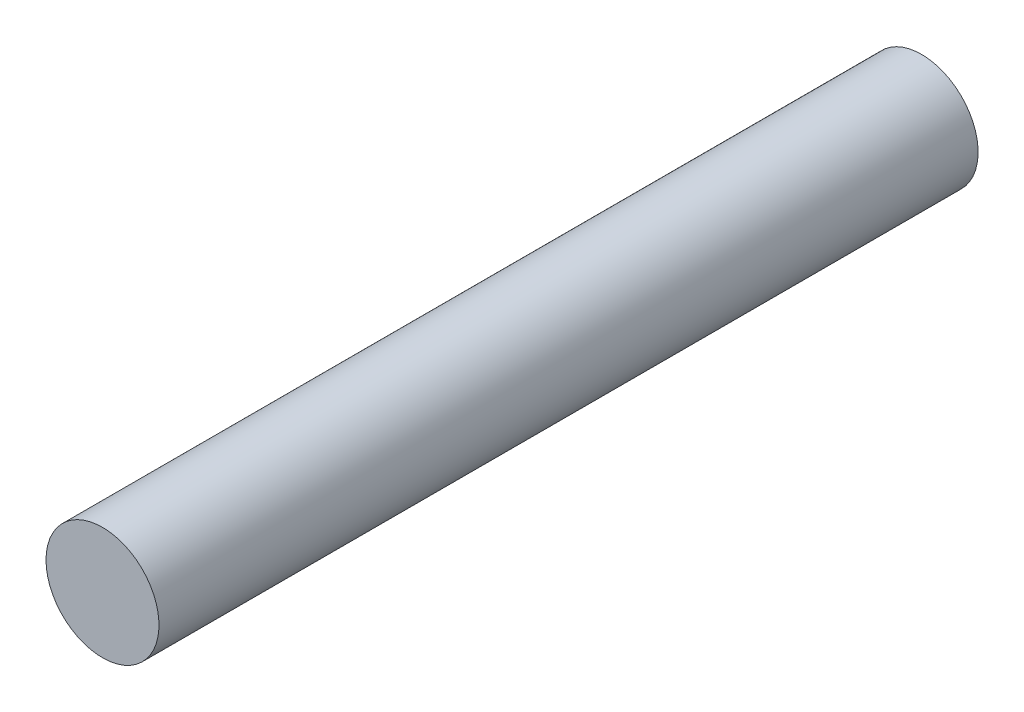
SolidWorks part; units mm, degrees
ref_plane "Front Plane" through (0, 0, 0) normal (0, 0, 1) x (1, 0, 0)
ref_plane "Top Plane" through (0, 0, 0) normal (0, 1, 0) x (1, 0, 0)
ref_plane "Right Plane" through (0, 0, 0) normal (1, 0, 0) x (0, 0, -1)
sketch "Sketch1" plane through (0, 0, 0) normal (0, 0, 1) x (1, 0, 0)
  circle A0 centre (0, 0) radius 4
  dimension "D1" = 8
extrude "Boss-Extrude1" add sketch "Sketch1" along normal blind 58
